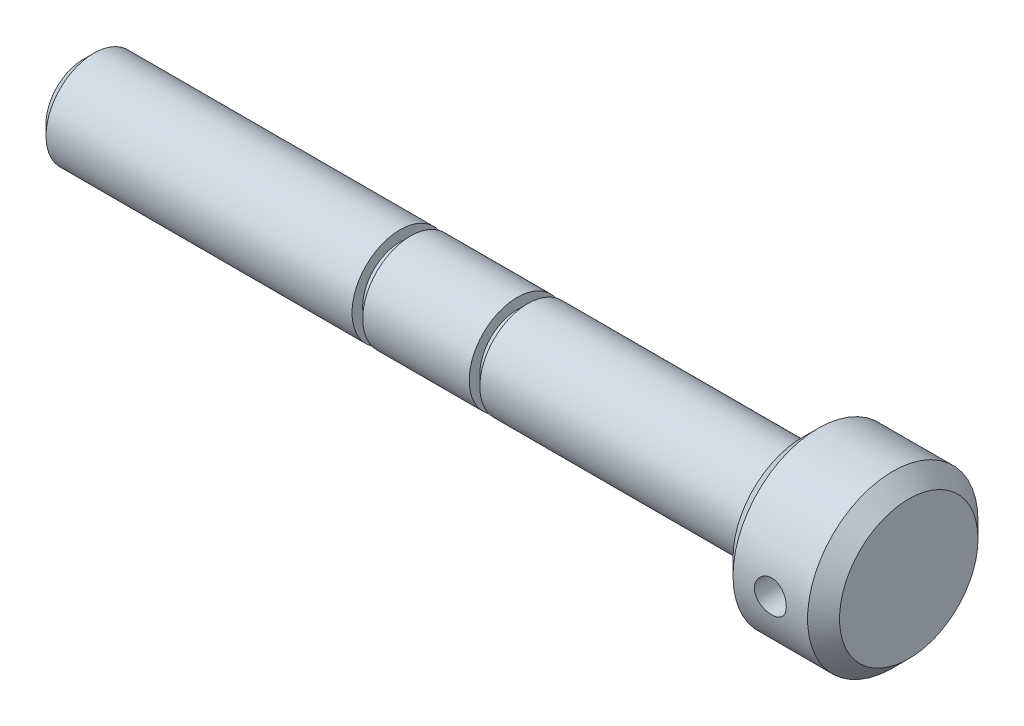
SolidWorks part; units mm, degrees
ref_plane "Front Plane" through (0, 0, 0) normal (0, 0, 1) x (1, 0, 0)
ref_plane "Top Plane" through (0, 0, 0) normal (0, 1, 0) x (1, 0, 0)
ref_plane "Right Plane" through (0, 0, 0) normal (1, 0, 0) x (0, 0, -1)
sketch "Sketch1" plane through (0, 0, 0) normal (0, 0, 1) x (1, 0, 0)
  line L0 (0, 0) -> (0, 9)
  line L1 (0, 9) -> (59.46, 9)
  line L2 (59.46, 9) -> (59.46, 7)
  line L3 (59.46, 7) -> (61.46, 7)
  line L4 (61.46, 7) -> (61.46, 9)
  line L5 (61.46, 9) -> (81.46, 9)
  line L6 (81.46, 9) -> (81.46, 7)
  line L7 (81.46, 7) -> (83.46, 7)
  line L8 (83.46, 7) -> (83.46, 9)
  line L9 (83.46, 9) -> (135, 9)
  line L10 (135, 9) -> (135, 16)
  line L11 (135, 16) -> (155, 16)
  line L12 (155, 16) -> (155, 0)
  line L13 (155, 0) -> (0, 0)
  dimension "D1" = 155
  dimension "D2" = 16
  dimension "D3" = 20
  dimension "D4" = 51.54
  dimension "D5" = 2
  dimension "D6" = 20
  dimension "D7" = 2
  dimension "D8" = 9
  dimension "D9" = 2
  dimension "D10" = 2
revolve "Revolve1" add sketch "Sketch1" angle 360 about L13
cosmetic thread "Cosmetic Thread2" parameters "D2"=15.252
chamfer "Chamfer1" distance 3 angle 45 1 edges at (155, 0, -16)
chamfer "Chamfer3" distance 3 angle 45 1 edges at (135, 0, -16)
chamfer "Chamfer4" distance 2 angle 45 1 edges at (0, 0, -9)
cosmetic thread "Cosmetic Thread1" parameters "D2"=15.252
sketch "Sketch2" plane through (0, 0, 0) normal (0, 0, 1) x (1, 0, 0)
  line L1 (152, 16) -> (138, 16) construction
  line L2 (135, 9) -> (135, -9) construction
  circle A0 centre (145, 0) radius 3
  dimension "D1" = 6
  dimension "D2" = 16
  dimension "D3" = 10
extrude "Cut-Extrude1" cut sketch "Sketch2" against normal mid plane 100
